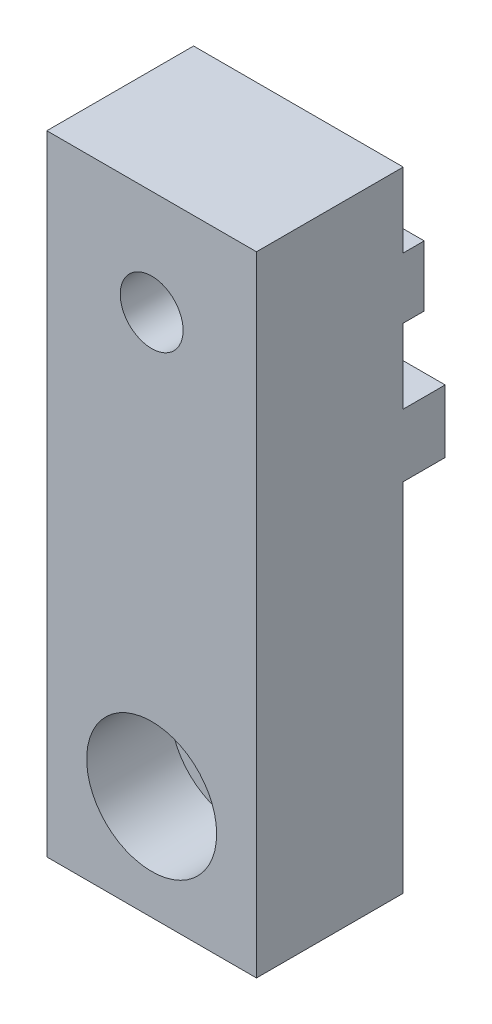
SolidWorks part; units mm, degrees
ref_plane "Front Plane" through (0, 0, 0) normal (0, 0, 1) x (1, 0, 0)
ref_plane "Top Plane" through (0, 0, 0) normal (0, 1, 0) x (1, 0, 0)
ref_plane "Right Plane" through (0, 0, 0) normal (1, 0, 0) x (0, 0, -1)
sketch "Sketch1" plane through (0, 0, 0) normal (0, 0, 1) x (1, 0, 0)
  line L1 (-5, -15) -> (5, -15)
  line L2 (-5, -15) -> (-5, 15)
  line L3 (-5, 15) -> (5, 15)
  line L4 (5, -15) -> (5, 15)
  line L5 (-5, -15) -> (5, 15) construction
  line L6 (-5, 15) -> (5, -15) construction
  point P0 (0, 0)
  dimension "D1" = 30
  dimension "D2" = 10
extrude "Main" add sketch "Sketch1" along normal blind 7
sketch "Sketch2" plane through (0, 0, 7) normal (0, 0, 1) x (1, 0, 0)
  line L0 (-5, -15) -> (5, -15) construction
  line L2 (5, -15) -> (5, 15) construction
  circle A0 centre (0, -10) radius 3.1
  point P7 (5, -5.4124)
  point P8 (5, -2.9855)
  dimension "D1" = 6.2
  dimension "D2" = 5
  dimension "D3" = 5
extrude "ShaftHole" cut sketch "Sketch2" against normal blind 4
sketch "Sketch3" plane through (0, 0, 0) normal (0, 0, -1) x (-1, 0, 0)
  line L2 (5, 15) -> (5, -15) construction
  line L3 (5, 11.45) -> (-5, 11.45)
  line L4 (5, 11.45) -> (5, 8.55)
  line L6 (5, 8.55) -> (-5, 8.55)
  line L7 (-5, 11.45) -> (-5, 8.55)
  line L8 (-5, -15) -> (-5, 15) construction
  line L9 (-5, 15) -> (5, 15) construction
  dimension "D1" = 2.9
  dimension "D2" = 3.55
extrude "Boss-Extrude1" add sketch "Sketch3" along normal blind 1
sketch "Sketch4" plane through (0, 0, 7) normal (0, 0, 1) x (1, 0, 0)
  line L0 (5, 15) -> (-5, 15) construction
  circle A0 centre (0, 10) radius 1.5
  point P4 (0, 0)
  point P6 (5, 10.4038)
  point P7 (5, 10.7926)
  dimension "D1" = 3
  dimension "D2" = 5
extrude "Cut-Extrude1" cut sketch "Sketch4" against normal through all
sketch "Sketch5" plane through (0, 0, 0) normal (0, 0, -1) x (-1, 0, 0)
  line L0 (-5, -15) -> (-5, 8.55) construction
  line L1 (-5, 2) -> (5, 2)
  line L2 (-5, 2) -> (-5, 5)
  line L3 (-5, 5) -> (5, 5)
  line L4 (5, 2) -> (5, 5)
  line L5 (5, 8.55) -> (5, -15) construction
  line L6 (-5, 15) -> (5, 15) construction
  dimension "D1" = 10
  dimension "D2" = 3
extrude "Boss-Extrude2" add sketch "Sketch5" along normal blind 2
